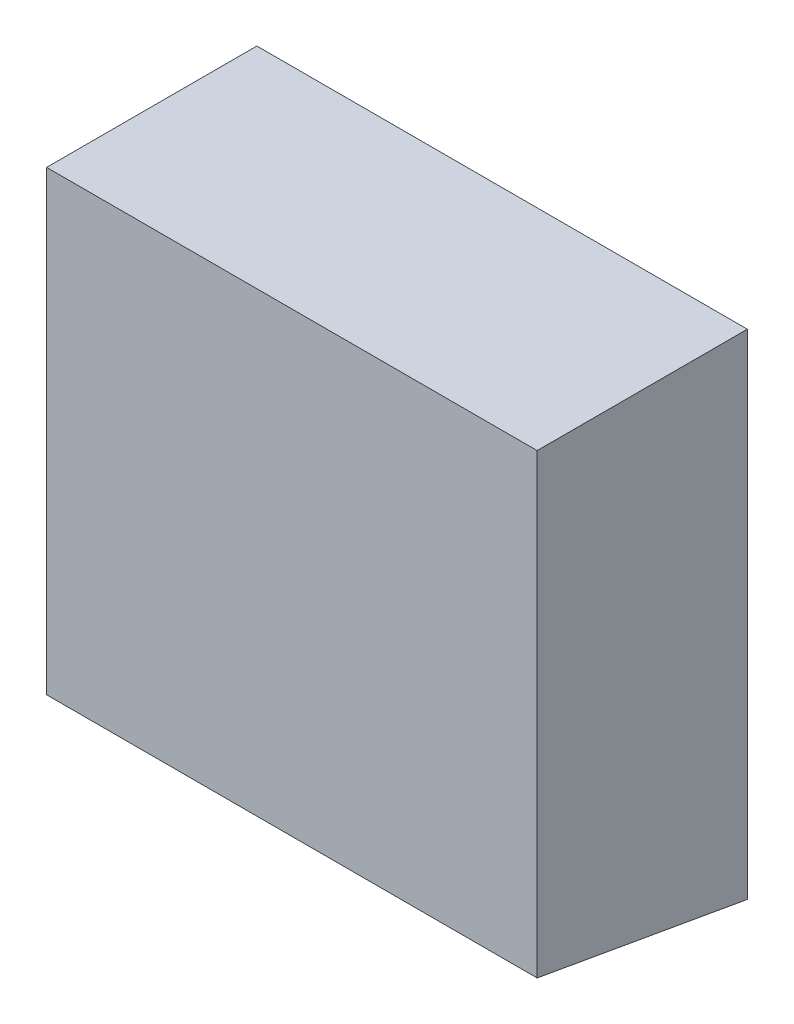
SolidWorks part; units mm, degrees
material "Pine"
ref_plane "Front Plane" through (0, 0, 0) normal (0, 0, 1) x (1, 0, 0)
ref_plane "Top Plane" through (0, 0, 0) normal (0, 1, 0) x (1, 0, 0)
ref_plane "Right Plane" through (0, 0, 0) normal (1, 0, 0) x (0, 0, -1)
sketch "Sketch1" plane through (0, 0, 0) normal (0, 1, 0) x (1, 0, 0)
  line L1 (-44.45, 19.05) -> (44.45, 19.05)
  line L2 (-44.45, 19.05) -> (-44.45, -19.05)
  line L4 (44.45, 19.05) -> (44.45, -19.05)
  line L5 (-44.45, 19.05) -> (44.45, -19.05) construction
  line L6 (-44.45, -19.05) -> (44.45, 19.05) construction
  line L7 (-44.45, -19.05) -> (44.45, -19.05)
  point P0 (0, 0)
  dimension "D1" = 88.9
  dimension "D2" = 38.1
extrude "Boss-Extrude1" add sketch "Sketch1" along normal blind 89.5 contours L2 L4 L1
sketch "Sketch2" plane through (-44.45, 0, 0) normal (-1, 0, 0) x (0, 0, 1)
  line L0 (-19.05, 0) -> (19.05, 6.7181)
  line L1 (19.05, 89.5) -> (19.05, 0) construction
  line L2 (19.05, 6.7181) -> (19.05, 0)
  line L3 (19.05, 0) -> (-19.05, 0)
  dimension "D1" = 10
extrude "Cut-Extrude1" cut sketch "Sketch2" against normal up to next
